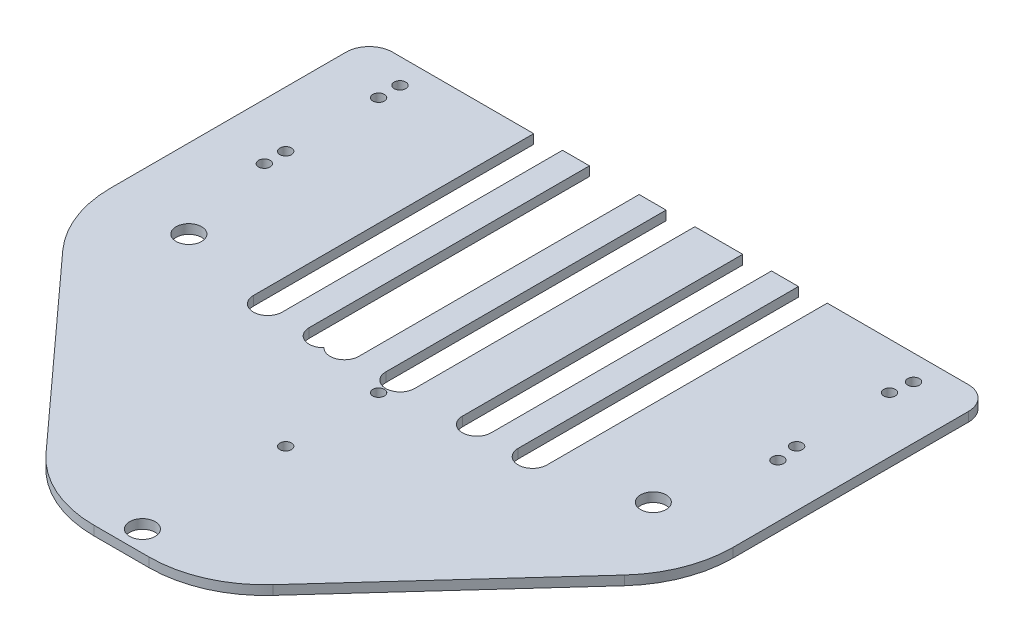
SolidWorks part; units mm, degrees
material "6061 Alloy"
ref_plane "Front Plane" through (0, 0, 0) normal (0, 0, 1) x (1, 0, 0)
ref_plane "Top Plane" through (0, 0, 0) normal (0, 1, 0) x (1, 0, 0)
ref_plane "Right Plane" through (0, 0, 0) normal (1, 0, 0) x (0, 0, -1)
sketch "Sketch1" plane through (0, 0, 0) normal (0, 1, 0) x (1, 0, 0)
  line L1 (0, 0) -> (134, 0)
  line L2 (0, 0) -> (0, 120.35)
  line L3 (0, 120.35) -> (134, 120.35)
  line L4 (134, 0) -> (134, 120.35)
  dimension "D1" = 134
  dimension "D2" = 120.35
extrude "Boss-Extrude1" add sketch "Sketch1" along normal blind 2
sketch "Sketch3" plane through (0, 2, 0) normal (0, 1, 0) x (1, 0, 0)
  line L0 (86.6, 120.35) -> (86.6, 60)
  line L2 (86.6, 120.35) -> (80.4, 120.35)
  line L3 (80.4, 120.35) -> (80.4, 60)
  line L4 (70.1, 120.35) -> (70.1, 60)
  line L5 (70.1, 120.35) -> (63.9, 120.35)
  line L6 (63.9, 120.35) -> (63.9, 60)
  line L7 (98.6, 120.35) -> (98.6, 60)
  line L8 (98.6, 120.35) -> (92.4, 120.35)
  line L9 (92.4, 120.35) -> (92.4, 60)
  line L10 (58.1, 120.35) -> (58.1, 60)
  line L11 (58.1, 120.35) -> (51.9, 120.35)
  line L12 (51.9, 120.35) -> (51.9, 60)
  line L16 (41.6, 120.35) -> (41.6, 60)
  line L17 (41.6, 120.35) -> (35.4, 120.35)
  line L18 (35.4, 120.35) -> (35.4, 60)
  line L19 (134, 120.35) -> (0, 120.35) construction
  line L23 (134, 0) -> (134, 120.35) construction
  arc A0 (80.4, 60) -> (86.6, 60) centre (83.5, 60) ccw
  arc A1 (63.9, 60) -> (70.1, 60) centre (67, 60) ccw
  arc A2 (92.4, 60) -> (98.6, 60) centre (95.5, 60) ccw
  arc A3 (51.9, 60) -> (58.1, 60) centre (55, 60) ccw
  arc A5 (35.4, 60) -> (41.6, 60) centre (38.5, 60) ccw
  dimension "D1" = 3.1
  dimension "D2" = 16.5
  dimension "D4" = 12
  dimension "D5" = 16.5
  dimension "D6" = 12
  dimension "D7" = 60.35
  dimension "D8" = 38.5
extrude "Cut-Extrude1" cut sketch "Sketch3" against normal through all
sketch "Sketch4" plane through (0, 2, 0) normal (0, 1, 0) x (1, 0, 0)
  line L0 (47.4, 120.35) -> (53.6, 120.35)
  line L1 (51.9, 120.35) -> (41.6, 120.35) construction
  line L2 (53.6, 120.35) -> (53.6, 60)
  line L3 (47.4, 120.35) -> (47.4, 60)
  line L4 (41.6, 60) -> (41.6, 120.35) construction
  arc A0 (47.4, 60) -> (53.6, 60) centre (50.5, 60) ccw
  arc A1 (51.9, 60) -> (58.1, 60) centre (55, 60) ccw construction
  dimension "D1" = 4.5
extrude "Cut-Extrude2" cut sketch "Sketch4" against normal through all
hole_wizard "linear bearing" positions "Sketch6" profile "Sketch5" tap size "M3x0.5" standard "ANSI Metric" end condition through all
sketch "Sketch6" plane through (0, 2, 0) normal (0, 1, 0) x (1, 0, 0)
  line L0 (134, 0) -> (134, 120.35) construction
  line L6 (0, 120.35) -> (0, 0) construction
  line L9 (35.4, 120.35) -> (0, 120.35) construction
  point P36 (12, 110.35)
  point P38 (12, 90.35)
  point P40 (122, 110.35)
  point P42 (122, 90.35)
  point P44 (67, 55.35)
  point P46 (67, 35.35)
  dimension "D1" = 67
  dimension "D2" = 12
  dimension "D3" = 10
  dimension "D4" = 12
  dimension "D5" = 20
  dimension "D6" = 35
  dimension "D7" = 20
sketch "Sketch5" plane through (12, 2, -110.35) normal (1, 0, 0) x (0, 0, 1)
  line L0 (0, 0) -> (0, 2)
  line L1 (0, 2) -> (1.25, 2)
  line L2 (1.25, 2) -> (1.25, 0)
  line L5 (1.25, 0) -> (0, 0)
  line L11 (0, -6.35) -> (0, 107.95) construction
  dimension "Thread Major Dia." = 2.5
  dimension "Thru Tap Drill Depth" = 2
hole_wizard "belt holders" positions "Sketch8" profile "Sketch7" tap size "M3x0.5" standard "ANSI Metric" end condition through all
sketch "Sketch8" plane through (0, 2, 0) normal (0, 1, 0) x (1, 0, 0)
  line L0 (0, 120.35) -> (0, 0) construction
  circle A0 centre (12, 110.35) radius 1.25 construction
  circle A1 centre (12, 90.35) radius 1.25 construction
  point P0 (12, 114.95)
  point P2 (12, 85.75)
  point P4 (122.5813, 85.75)
  point P6 (122.5813, 114.95)
  dimension "D2" = 4.6
  dimension "D1" = 12
  dimension "D3" = 4.6
cosmetic thread "Hole Thread1" parameters "D2"=3
cosmetic thread "Hole Thread2" parameters "D2"=3
cosmetic thread "Hole Thread3" parameters "D2"=3
cosmetic thread "Hole Thread4" parameters "D2"=3
sketch "Sketch7" plane through (12, 2, -114.95) normal (1, 0, 0) x (0, 0, 1)
  line L0 (0, 0) -> (0, 2)
  line L1 (0, 2) -> (1.25, 2)
  line L2 (1.25, 2) -> (1.25, 0)
  line L5 (1.25, 0) -> (0, 0)
  line L11 (0, -6.35) -> (0, 107.95) construction
  dimension "Thru Tap Drill Dia." = 2.5
  dimension "Thru Tap Drill Depth" = 2
sketch "Sketch9" plane through (0, 2, 0) normal (0, 1, 0) x (1, 0, 0)
  line L0 (0, 55) -> (50, 0)
  line L1 (0, 120.35) -> (0, 0) construction
  line L2 (0, 0) -> (134, 0) construction
  line L3 (50, 0) -> (0, 0)
  line L4 (0, 0) -> (0, 55)
  line L5 (134, 0) -> (134, 55)
  line L6 (134, 0) -> (134, 120.35) construction
  line L7 (134, 55) -> (84, 0)
  line L8 (84, 0) -> (134, 0)
  dimension "D1" = 50
  dimension "D2" = 55
extrude "Cut-Extrude3" cut sketch "Sketch9" against normal through all
fillet "Fillet1" radius 5 2 edges at (134, 1, -120.35) (0, 1, -120.35)
fillet "Fillet2" radius 25 4 edges at (134, 1, -55) (84, 1, 0) (50, 1, 0) (0, 1, -55)
hole_wizard "Ø5.5 (5.5) Diameter Hole1" positions "Sketch11" profile "Sketch10" hole size "Ø5.5" standard "ANSI Metric" end condition through all
sketch "Sketch11" plane through (0, 2, 0) normal (0, 1, 0) x (1, 0, 0)
  line L0 (134, 64.6652) -> (134, 115.35) construction
  line L1 (61.0592, 0) -> (72.9408, 0) construction
  point P0 (67, 4.5)
  point P2 (117, 64.5)
  point P4 (17, 64.5)
  dimension "D1" = 67
  dimension "D2" = 50
  dimension "D3" = 50
  dimension "D4" = 60
  dimension "D5" = 4.5
sketch "Sketch10" plane through (67, 2, -4.5) normal (1, 0, 0) x (0, 0, 1)
  line L0 (0, 0) -> (0, 2)
  line L1 (0, 2) -> (2.75, 2)
  line L2 (2.75, 2) -> (2.75, 0)
  line L5 (2.75, 0) -> (0, 0)
  line L11 (0, -6.35) -> (0, 107.95) construction
  dimension "Thru Hole Dia." = 5.5
  dimension "Thru Hole Depth" = 2
